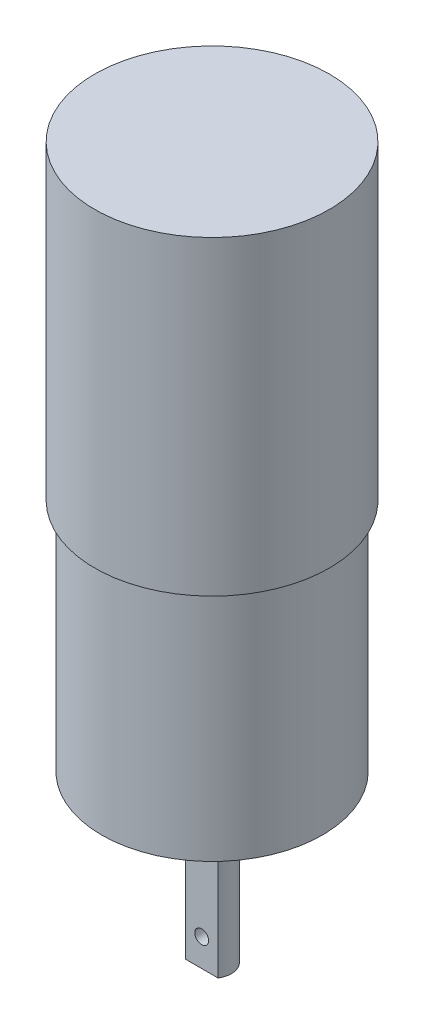
SolidWorks part; units mm, degrees
ref_plane "Front Plane" through (0, 0, 0) normal (0, 0, 1) x (1, 0, 0)
ref_plane "Top Plane" through (0, 0, 0) normal (0, 1, 0) x (1, 0, 0)
ref_plane "Right Plane" through (0, 0, 0) normal (1, 0, 0) x (0, 0, -1)
sketch "Sketch1" plane through (0, 0, 0) normal (0, 1, 0) x (1, 0, 0)
  circle A0 centre (0, 0) radius 8
  dimension "D1" = 16
extrude "Boss-Extrude1" add sketch "Sketch1" along normal blind 17
sketch "Sketch2" plane through (0, 17, 0) normal (0, 1, 0) x (1, 0, 0)
  circle A0 centre (0, 0) radius 8.5
  dimension "D1" = 17
extrude "Boss-Extrude2" add sketch "Sketch2" along normal blind 22.5
sketch "Sketch3" plane through (0, 0, 0) normal (0, -1, 0) x (1, 0, 0)
  circle A0 centre (0, 0) radius 3
  dimension "D1" = 6
extrude "Boss-Extrude3" add sketch "Sketch3" along normal blind 2
sketch "Sketch4" plane through (0, -2, 0) normal (0, -1, 0) x (1, 0, 0)
  circle A0 centre (0, 0) radius 1.4
  dimension "D1" = 2.8
extrude "Boss-Extrude4" add sketch "Sketch4" along normal blind 10 contours A0
sketch "Sketch5" plane through (0, -12, 0) normal (0, -1, 0) x (1, 0, 0)
  line L0 (-1.1822, 0.75) -> (1.1822, 0.75)
  circle A0 centre (0, 0) radius 1.4 construction
  arc A1 (1.1822, 0.75) -> (-1.1822, 0.75) centre (0, 0) ccw
  dimension "D1" = 0.75
extrude "Cut-Extrude1" cut sketch "Sketch5" against normal offset from surface (8.5 mm away) 1.5 up to face at (0, -2, -1.4)
sketch "Sketch6" plane through (0, 0, 0.75) normal (0, 0, 1) x (1, 0, 0)
  line L0 (-1.1822, -12) -> (1.1822, -12) construction
  circle A0 centre (0, -10) radius 0.5
  point P4 (0, 0)
  point P5 (0, -12)
  dimension "D2" = 1
  dimension "D1" = 2
extrude "Cut-Extrude2" cut sketch "Sketch6" against normal up to next
